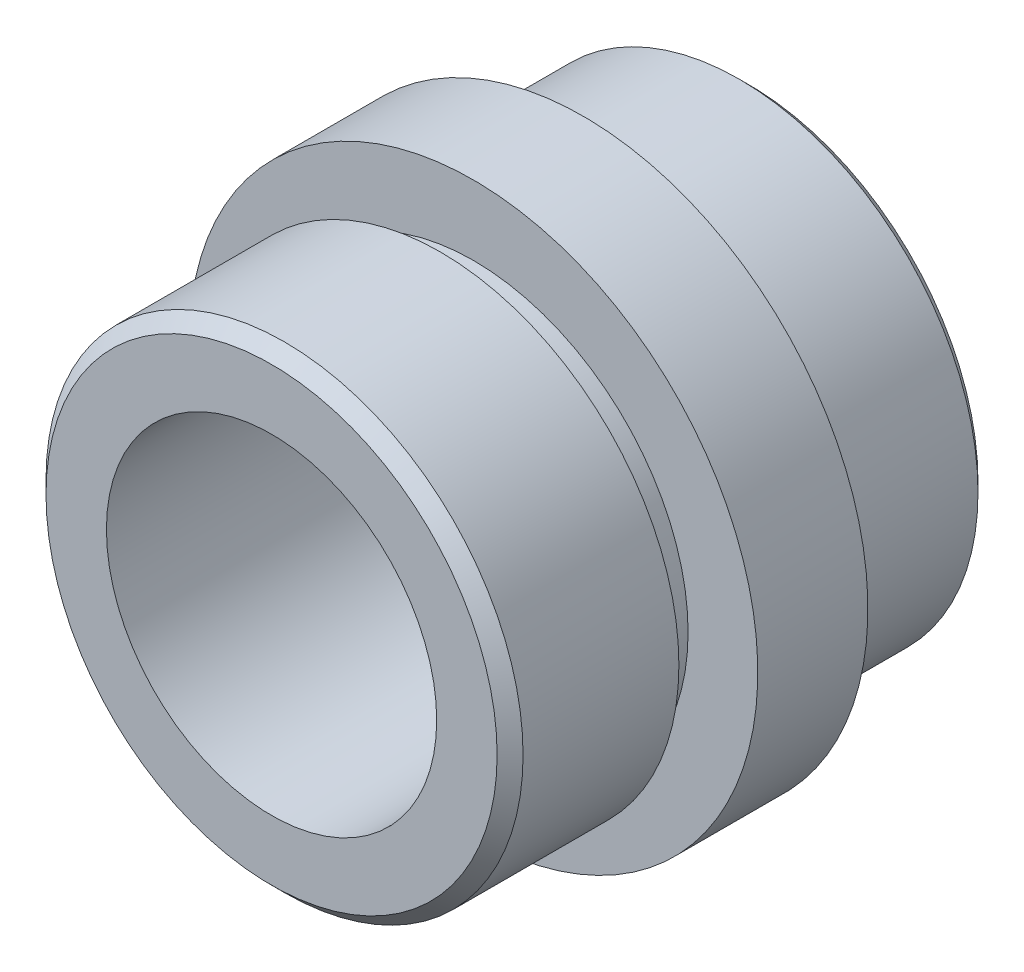
SolidWorks part; units mm, degrees
ref_plane "Спереди" through (0, 0, 0) normal (0, 0, 1) x (1, 0, 0)
ref_plane "Сверху" through (0, 0, 0) normal (0, 1, 0) x (1, 0, 0)
ref_plane "Справа" through (0, 0, 0) normal (1, 0, 0) x (0, 0, -1)
ref_plane "Плоскость4" through (0, 0, 0) normal (0, -1, 0) x (1, 0, 0)
sketch "Эскиз1" plane through (0, 0, 0) normal (0, -1, 0) x (1, 0, 0)
  line L0 (11.7, 16.8) -> (13, 16.8)
  line L1 (13, 16.8) -> (13, 25.2929)
  line L2 (13, 25.2929) -> (12.2929, 26)
  line L3 (12.2929, 26) -> (9, 26)
  line L4 (9, 26) -> (9, 1)
  line L5 (9, 1) -> (10, 0)
  line L6 (10, 0) -> (12.5, 0)
  line L7 (12.5, 0) -> (13, 0.5)
  line L8 (13, 0.5) -> (13, 7.7)
  line L9 (13, 7.7) -> (11.7, 7.7)
  line L10 (11.7, 7.7) -> (11.7, 9)
  line L11 (11.7, 9) -> (15.5, 9)
  line L12 (15.5, 9) -> (15.5, 15)
  line L13 (15.5, 15) -> (11.7, 15)
  line L14 (11.7, 15) -> (11.7, 16.8)
  line L15 (0, 26.005) -> (0, -0.005) construction
revolve "Повернуть1" add sketch "Эскиз1" angle 360 about L15
